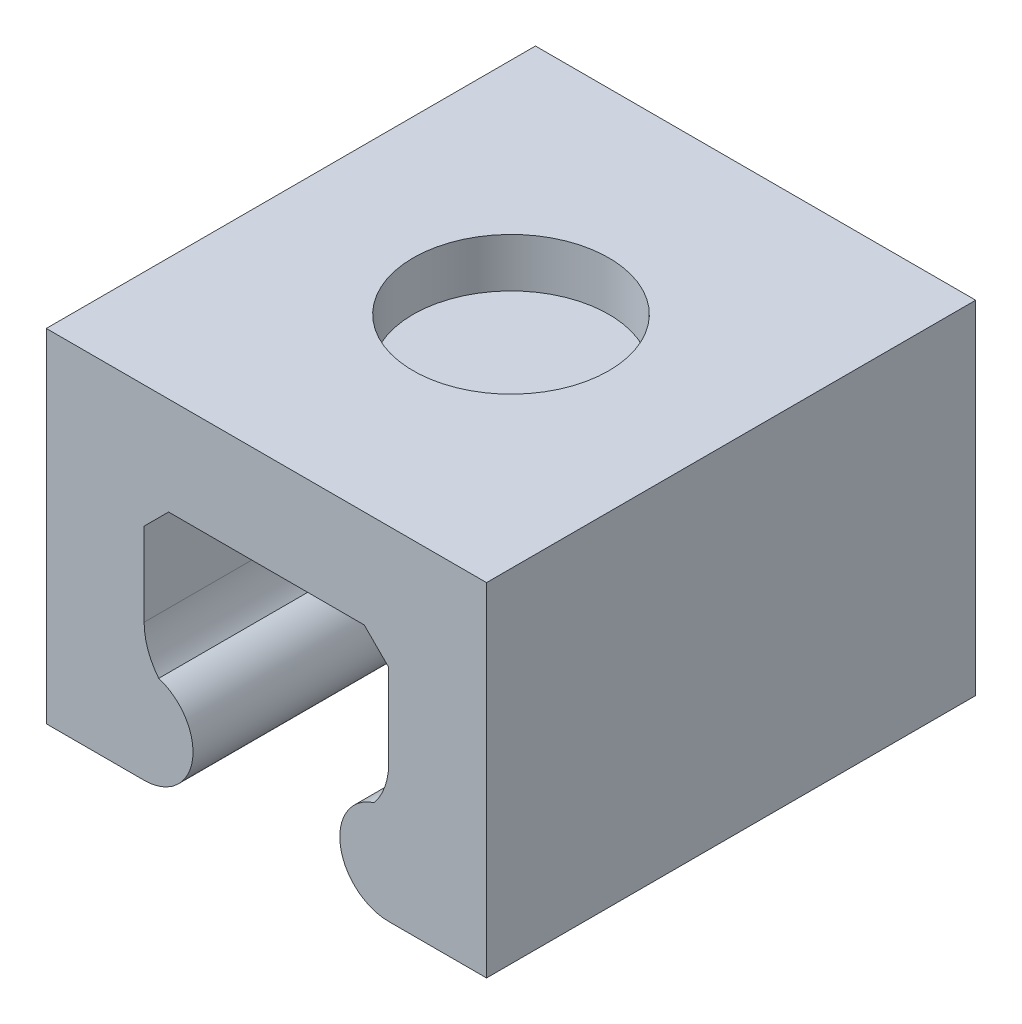
SolidWorks part; units mm, degrees
ref_plane "Front Plane" through (0, 0, 0) normal (0, 0, 1) x (1, 0, 0)
ref_plane "Top Plane" through (0, 0, 0) normal (0, 1, 0) x (1, 0, 0)
ref_plane "Right Plane" through (0, 0, 0) normal (1, 0, 0) x (0, 0, -1)
sketch "Sketch1" plane through (0, 0, 0) normal (0, 0, 1) x (1, 0, 0)
  line L5 (2.5, 1.7982) -> (2.5, 3.5)
  line L6 (2.5, 3.5) -> (2, 4)
  line L7 (-2.5, 3.5) -> (-2.5, 1.7982)
  line L8 (-2, 4) -> (-2.5, 3.5)
  line L9 (2, 4) -> (-2, 4)
  line L11 (2.5, -1) -> (4.5, -1)
  line L12 (4.5, -1) -> (4.5, 6)
  line L13 (4.5, 6) -> (-4.5, 6)
  line L14 (-4.5, 6) -> (-4.5, -1)
  line L15 (-4.5, -1) -> (-2.5, -1)
  arc A4 (-2.5, -1) -> (-2.2014, 0.9544) centre (-2.5, 0) ccw
  arc A5 (2.2014, 0.9544) -> (2.5, -1) centre (2.5, 0) ccw
  arc A6 (2.2014, 0.9544) -> (2.5, 1.7982) centre (1.1583, 1.7982) ccw
  arc A7 (-2.5, 1.7982) -> (-2.2014, 0.9544) centre (-1.1583, 1.7982) ccw
  dimension "D1" = 2
  dimension "D2" = 2
  dimension "D3" = 2
extrude "Boss-Extrude1" add sketch "Sketch1" along normal blind 10 contours L14 L15 A4 A7 L7 L8 L9 L6 L5 A6 A5 L11 L12 L13
sketch "Sketch2" plane through (0, 6, 0) normal (0, 1, 0) x (1, 0, 0)
  line L0 (-4.5, -10) -> (-4.5, 0) construction
  line L1 (4.5, -10) -> (-4.5, -10) construction
  circle A0 centre (0, -5) radius 2
  point P4 (-4.5, -5)
  dimension "D1" = 4.5
  dimension "D2" = 5
extrude "Cut-Extrude1" cut sketch "Sketch2" against normal blind 1
